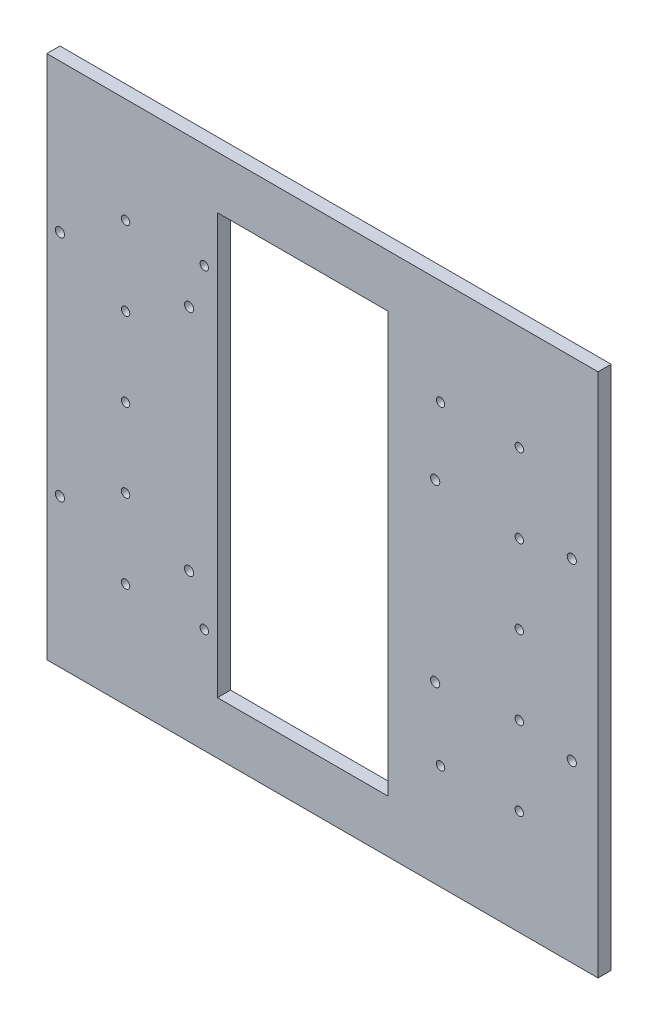
SolidWorks part; units mm, degrees
ref_plane "前视基准面" through (0, 0, 0) normal (0, 0, 1) x (1, 0, 0)
ref_plane "上视基准面" through (0, 0, 0) normal (0, 1, 0) x (1, 0, 0)
ref_plane "右视基准面" through (0, 0, 0) normal (1, 0, 0) x (0, 0, -1)
other "Configuration Table"
sketch "草图1" plane through (0, 0, 0) normal (0, 0, 1) x (1, 0, 0)
  line L4 (25.05, -79.5709) -> (25.05, 80.4291)
  line L5 (-39.95, -79.5709) -> (25.05, -79.5709)
  line L6 (-39.95, 80.4291) -> (-39.95, -79.5709)
  line L7 (25.05, 80.4291) -> (-39.95, 80.4291)
  line L8 (-84.95, 100.4291) -> (-84.95, -99.5709)
  line L9 (-84.95, -99.5709) -> (85.05, -99.5709)
  line L10 (85.05, -99.5709) -> (85.05, 100.4291)
  line L11 (85.05, 100.4291) -> (-84.95, 100.4291)
  circle A18 centre (-74.95, 60.4291) radius 1.6
  circle A19 centre (-74.95, -59.5709) radius 1.6
  circle A20 centre (75.05, -59.5709) radius 1.6
  circle A21 centre (75.05, 60.4291) radius 1.6
  circle A22 centre (75.05, 30.4291) radius 1.6
  circle A23 centre (-74.95, 30.4291) radius 1.6
  circle A24 centre (45.05, -59.5709) radius 1.6
  circle A25 centre (-74.95, 0.4291) radius 1.6
  circle A26 centre (75.05, 0.4291) radius 1.6
  circle A27 centre (-74.95, -29.5709) radius 1.6
  circle A28 centre (75.05, -29.5709) radius 1.6
  circle A29 centre (-44.95, -59.5709) radius 1.6
  circle A30 centre (45.05, 60.4291) radius 1.6
  circle A31 centre (-44.95, 60.4291) radius 1.6
extrude "凸台-拉伸1" add sketch "草图1" along normal blind 5
sketch "草图5" plane through (-84.95, 0, 0) normal (-1, 0, 0) x (0, 0, 1)
  line L4 (0, 100.4291) -> (0, -99.5709)
  line L5 (0, -99.5709) -> (5, -99.5709)
  line L6 (5, -99.5709) -> (5, 100.4291)
  line L7 (5, 100.4291) -> (0, 100.4291)
  line L8 (0, 100.4291) -> (0, -99.5709)
  line L9 (0, -99.5709) -> (5, -99.5709)
  line L10 (5, -99.5709) -> (5, 100.4291)
  line L11 (5, 100.4291) -> (0, 100.4291)
  dimension "D1" = 0
extrude "凸台-拉伸2" add sketch "草图5" along normal blind 20
sketch "草图4" plane through (0, 0, 5) normal (0, 0, 1) x (1, 0, 0)
  line L1 (-99.95, 43.9691) -> (-50.74, 43.9691)
  line L2 (-99.95, 43.9691) -> (-99.95, -43.1109)
  line L3 (-99.95, -43.1109) -> (-50.74, -43.1109)
  line L4 (-50.74, 43.9691) -> (-50.74, -43.1109)
  line L5 (85.05, 100.4291) -> (-104.95, 100.4291) construction
  line L8 (-104.95, -99.5709) -> (-104.95, 100.4291) construction
  circle A0 centre (-99.95, 43.9691) radius 1.75
  circle A1 centre (-50.74, 43.9691) radius 1.75
  circle A2 centre (-99.95, -43.1109) radius 1.75
  circle A3 centre (-50.74, -43.1109) radius 1.75
  dimension "D5" = 3.5
  dimension "D6" = 3.5
  dimension "D7" = 3.5
  dimension "D8" = 3.5
  dimension "D1" = 87.08
  dimension "D2" = 5
  dimension "D3" = 49.21
  dimension "D4" = 56.46
extrude "切除-拉伸1" cut sketch "草图4" against normal blind 30 contours L1 A0 L2 | L2 A0 L1 | L2 A2 L3 | L3 A2 L2 | L4 A3 L3 | L3 A3 L4 | A1
sketch "草图6" plane through (85.05, 0, 0) normal (1, 0, 0) x (0, 0, -1)
  line L4 (0, -99.5709) -> (0, 100.4291)
  line L5 (0, 100.4291) -> (-5, 100.4291)
  line L6 (-5, 100.4291) -> (-5, -99.5709)
  line L7 (-5, -99.5709) -> (0, -99.5709)
  line L8 (0, -99.5709) -> (0, 100.4291)
  line L9 (0, 100.4291) -> (-5, 100.4291)
  line L10 (-5, 100.4291) -> (-5, -99.5709)
  line L11 (-5, -99.5709) -> (0, -99.5709)
  dimension "D1" = 0
extrude "凸台-拉伸3" add sketch "草图6" along normal blind 20
sketch "草图7" plane through (0, 0, 5) normal (0, 0, 1) x (1, 0, 0)
  line L0 (105.05, 100.4291) -> (-104.95, 100.4291) construction
  line L1 (43, 33.7791) -> (95.05, 33.7791)
  line L2 (43, 33.7791) -> (43, -32.9209)
  line L3 (43, -32.9209) -> (95.05, -32.9209)
  line L4 (95.05, 33.7791) -> (95.05, -32.9209)
  line L7 (105.05, 100.4291) -> (105.05, -99.5709) construction
  circle A0 centre (43, 33.7791) radius 1.75
  circle A1 centre (43, -32.9209) radius 1.75
  circle A2 centre (95.05, 33.7791) radius 1.75
  circle A3 centre (95.05, -32.9209) radius 1.75
  dimension "D5" = 3.5
  dimension "D6" = 3.5
  dimension "D7" = 3.5
  dimension "D8" = 3.5
  dimension "D1" = 66.7
  dimension "D2" = 52.05
  dimension "D3" = 66.65
  dimension "D4" = 10
extrude "切除-拉伸2" cut sketch "草图7" against normal blind 20 contours L1 A0 L2 | L2 A0 L1 | L2 A1 L3 | L3 A1 L2 | L4 A3 L3 | L3 A3 L4 | L1 A2 L4 | L4 A2 L1
sketch "草图8" plane through (0, 0, 5) normal (0, 0, 1) x (1, 0, 0)
  line L4 (-39.95, 80.4291) -> (-39.95, -79.5709)
  line L5 (25.05, 80.4291) -> (-39.95, 80.4291)
  line L6 (25.05, -79.5709) -> (25.05, 80.4291)
  line L7 (-39.95, -79.5709) -> (25.05, -79.5709)
  line L8 (-39.95, 80.4291) -> (-39.95, -79.5709)
  line L9 (25.05, 80.4291) -> (-39.95, 80.4291)
  line L10 (25.05, -79.5709) -> (25.05, 80.4291)
  line L11 (-39.95, -79.5709) -> (25.05, -79.5709)
  line L12 (105.05, 100.4291) -> (-104.95, 100.4291)
  line L13 (-104.95, 100.4291) -> (-104.95, -99.5709)
  line L14 (-104.95, -99.5709) -> (105.05, -99.5709)
  line L15 (105.05, -99.5709) -> (105.05, 100.4291)
  line L16 (105.05, 100.4291) -> (-104.95, 100.4291)
  line L17 (-104.95, 100.4291) -> (-104.95, -99.5709)
  line L18 (-104.95, -99.5709) -> (105.05, -99.5709)
  line L19 (105.05, -99.5709) -> (105.05, 100.4291)
  circle A1 centre (95.05, 33.7791) radius 1.75
  circle A2 centre (95.05, 33.7791) radius 1.75
  circle A3 centre (-74.95, -59.5709) radius 1.6
  circle A4 centre (-74.95, -59.5709) radius 1.6
  circle A5 centre (75.05, 60.4291) radius 1.6
  circle A6 centre (75.05, 60.4291) radius 1.6
  circle A7 centre (-74.95, 30.4291) radius 1.6
  circle A8 centre (-74.95, 30.4291) radius 1.6
  circle A9 centre (-74.95, 0.4291) radius 1.6
  circle A10 centre (-74.95, 0.4291) radius 1.6
  circle A11 centre (-74.95, -29.5709) radius 1.6
  circle A12 centre (-74.95, -29.5709) radius 1.6
  circle A13 centre (-44.95, -59.5709) radius 1.6
  circle A14 centre (-44.95, -59.5709) radius 1.6
  circle A15 centre (-44.95, 60.4291) radius 1.6
  circle A16 centre (-44.95, 60.4291) radius 1.6
  circle A17 centre (95.05, -32.9209) radius 1.75
  circle A18 centre (95.05, -32.9209) radius 1.75
  circle A19 centre (43, -32.9209) radius 1.75
  circle A20 centre (43, -32.9209) radius 1.75
  circle A21 centre (43, 33.7791) radius 1.75
  circle A22 centre (43, 33.7791) radius 1.75
  circle A23 centre (-50.74, 43.9691) radius 1.75
  circle A24 centre (-50.74, 43.9691) radius 1.75
  circle A25 centre (-50.74, -43.1109) radius 1.75
  circle A26 centre (-50.74, -43.1109) radius 1.75
  circle A27 centre (-99.95, -43.1109) radius 1.75
  circle A28 centre (-99.95, -43.1109) radius 1.75
  circle A29 centre (-99.95, 43.9691) radius 1.75
  circle A30 centre (-99.95, 43.9691) radius 1.75
  circle A31 centre (45.05, 60.4291) radius 1.6
  circle A32 centre (45.05, 60.4291) radius 1.6
  circle A33 centre (75.05, -29.5709) radius 1.6
  circle A34 centre (75.05, -29.5709) radius 1.6
  circle A35 centre (75.05, 0.4291) radius 1.6
  circle A36 centre (75.05, 0.4291) radius 1.6
  circle A37 centre (45.05, -59.5709) radius 1.6
  circle A38 centre (45.05, -59.5709) radius 1.6
  circle A39 centre (75.05, 30.4291) radius 1.6
  circle A40 centre (75.05, 30.4291) radius 1.6
  circle A41 centre (75.05, -59.5709) radius 1.6
  circle A42 centre (75.05, -59.5709) radius 1.6
  circle A43 centre (-74.95, 60.4291) radius 1.6
  circle A44 centre (-74.95, 60.4291) radius 1.6
  dimension "D1" = 0
  dimension "D2" = 0
  dimension "D3" = 0
  dimension "D4" = 0
  dimension "D5" = 0
  dimension "D6" = 0
  dimension "D7" = 0
  dimension "D8" = 0
  dimension "D9" = 0
  dimension "D10" = 0
  dimension "D11" = 0
  dimension "D12" = 0
  dimension "D13" = 0
  dimension "D14" = 0
  dimension "D15" = 0
  dimension "D16" = 0
  dimension "D17" = 0
  dimension "D18" = 0
  dimension "D19" = 0
  dimension "D20" = 0
  dimension "D21" = 0
  dimension "D22" = 0
  dimension "D23" = 0
  dimension "D24" = 0
